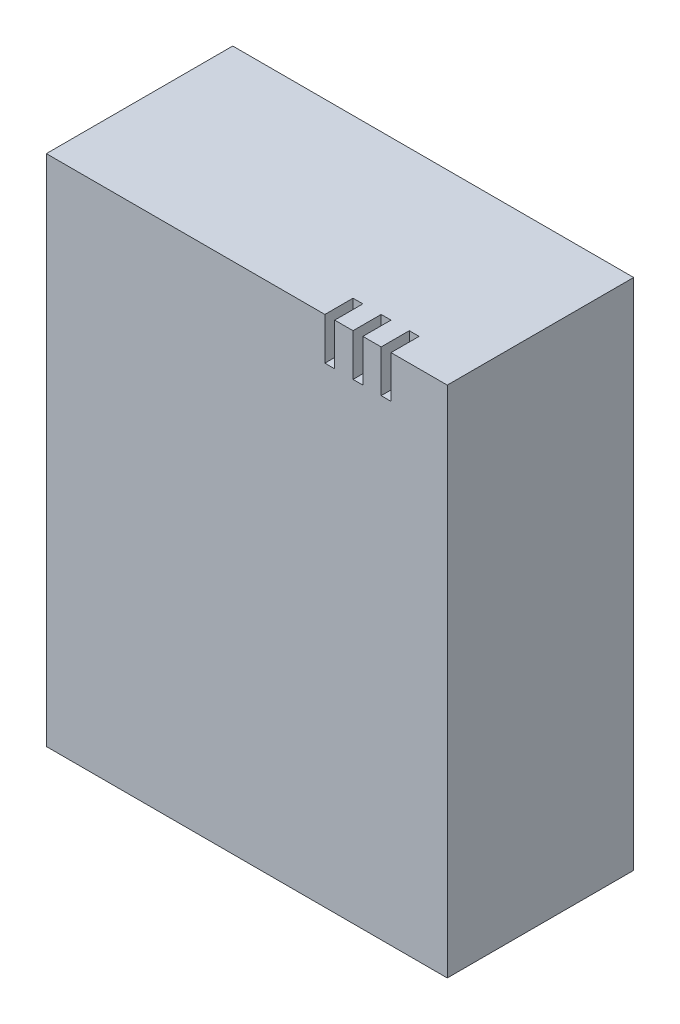
SolidWorks part; units mm, degrees
ref_plane "Front Plane" through (0, 0, 0) normal (0, 0, 1) x (1, 0, 0)
ref_plane "Top Plane" through (0, 0, 0) normal (0, 1, 0) x (1, 0, 0)
ref_plane "Right Plane" through (0, 0, 0) normal (1, 0, 0) x (0, 0, -1)
sketch "Sketch1" plane through (0, 0, 0) normal (0, 1, 0) x (1, 0, 0)
  line L1 (-14.25, -6.625) -> (14.25, -6.625)
  line L2 (-14.25, -6.625) -> (-14.25, 6.625)
  line L3 (-14.25, 6.625) -> (14.25, 6.625)
  line L4 (14.25, -6.625) -> (14.25, 6.625)
  line L5 (-14.25, -6.625) -> (14.25, 6.625) construction
  line L6 (-14.25, 6.625) -> (14.25, -6.625) construction
  point P0 (0, 0)
  dimension "D1" = 13.25
  dimension "D2" = 28.5
extrude "Boss-Extrude1" add sketch "Sketch1" along normal blind 36.5
sketch "Sketch2" plane through (0, 36.5, 0) normal (0, 1, 0) x (1, 0, 0)
  line L0 (-14.25, -6.625) -> (14.25, -6.625) construction
  line L1 (10.25, -6.625) -> (9.55, -6.625)
  line L2 (10.25, -6.625) -> (10.25, -4.625)
  line L3 (10.25, -4.625) -> (9.55, -4.625)
  line L4 (9.55, -6.625) -> (9.55, -4.625)
  line L5 (8.25, -6.625) -> (8.25, -4.625)
  line L6 (8.25, -4.625) -> (7.55, -4.625)
  line L7 (7.55, -6.625) -> (7.55, -4.625)
  line L8 (8.25, -6.625) -> (7.55, -6.625)
  line L9 (6.25, -6.625) -> (6.25, -4.625)
  line L10 (6.25, -4.625) -> (5.55, -4.625)
  line L11 (5.55, -6.625) -> (5.55, -4.625)
  line L12 (6.25, -6.625) -> (5.55, -6.625)
  line L13 (14.25, -6.625) -> (14.25, 6.625) construction
  dimension "D1" = 2
  dimension "D2" = 0.7
  dimension "D4" = 4
  dimension "D5" = 2
  dimension "D3" = 3
extrude "Cut-Extrude1" cut sketch "Sketch2" against normal blind 3
